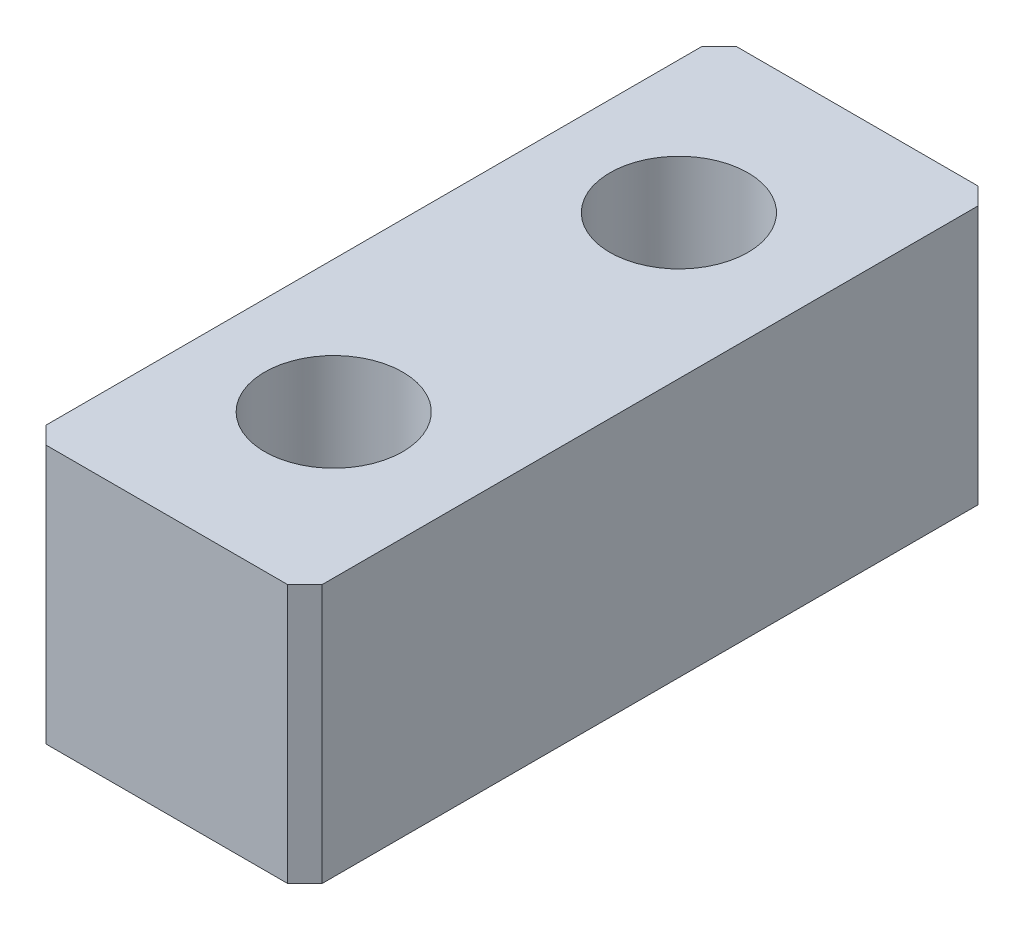
SolidWorks part; units mm, degrees
material "POM 乙缩醛共聚物"
ref_plane "前视基准面" through (0, 0, 0) normal (0, 0, 1) x (1, 0, 0)
ref_plane "上视基准面" through (0, 0, 0) normal (0, 1, 0) x (1, 0, 0)
ref_plane "右视基准面" through (0, 0, 0) normal (1, 0, 0) x (0, 0, -1)
sketch "草图1" plane through (0, 0, 0) normal (0, 0, 1) x (1, 0, 0)
  line L1 (4, 3.75) -> (-4, 3.75)
  line L2 (4, 3.75) -> (4, -3.75)
  line L3 (4, -3.75) -> (-4, -3.75)
  line L4 (-4, 3.75) -> (-4, -3.75)
  line L5 (4, 3.75) -> (-4, -3.75) construction
  line L6 (4, -3.75) -> (-4, 3.75) construction
  point P0 (0, 0)
  dimension "D1" = 7.5
  dimension "D2" = 8
extrude "凸台-拉伸1" add sketch "草图1" along normal mid plane 20
hole_wizard "Ø3.4 (3.4) 直径孔1" [suppressed] positions "草图3" profile "草图2" hole size "Ø3.4" standard "Gb"
sketch "草图3" plane through (0, 3.75, 0) normal (0, 1, 0) x (1, 0, 0)
  line L0 (-0.5, 5) -> (-0.5, -5) construction
  line L3 (0, 0) -> (-5.129, 0) construction
  line L6 (-4, -10) -> (-4, 10) construction
  point P0 (-0.5, 5)
  point P2 (-0.5, -5)
  dimension "D1" = 10
  dimension "D2" = 3.5
sketch "草图2" plane through (-0.5, 3.75, -5) normal (1, 0, 0) x (0, 0, 1)
  line L0 (0, 0) -> (0, 7.5)
  line L1 (0, 7.5) -> (1.7, 7.5)
  line L2 (1.7, 7.5) -> (1.7, 0)
  line L5 (1.7, 0) -> (0, 0)
  line L11 (0, -6.35) -> (0, 107.95) construction
  dimension "通孔孔直径" = 3.4
  dimension "通孔孔深度" = 7.5
chamfer "倒角1" distance 0.5 angle 45 4 edges at (4, 0, 10) (-4, 0, 10) (4, 0, -10) (-4, 0, -10)
hole_wizard "Ø4.0 (4) 直径孔1" positions "草图4" profile "草图5" hole size "Ø4.0" standard "Gb"
sketch "草图4" plane through (51.8, -3.75, -33) normal (0, -1, 0) x (-1, 0, 0)
  point P0 (51.965, -38)
  point P3 (51.965, -28)
sketch "草图5" plane through (-0.165, -3.75, 5) normal (1, 0, 0) x (0, 0, -1)
  line L0 (0, 0) -> (0, 8.7007)
  line L1 (0, 8.7007) -> (2, 7.499)
  line L2 (2, 7.499) -> (2, 0)
  line L3 (2, 0) -> (0, 0)
  line L4 (0, 8.7007) -> (-2, 7.499) construction
  line L5 (0, -6.35) -> (0, 107.95) construction
  dimension "孔直径" = 4
  dimension "孔深度" = 7.499
  dimension "导头角度" = 118
